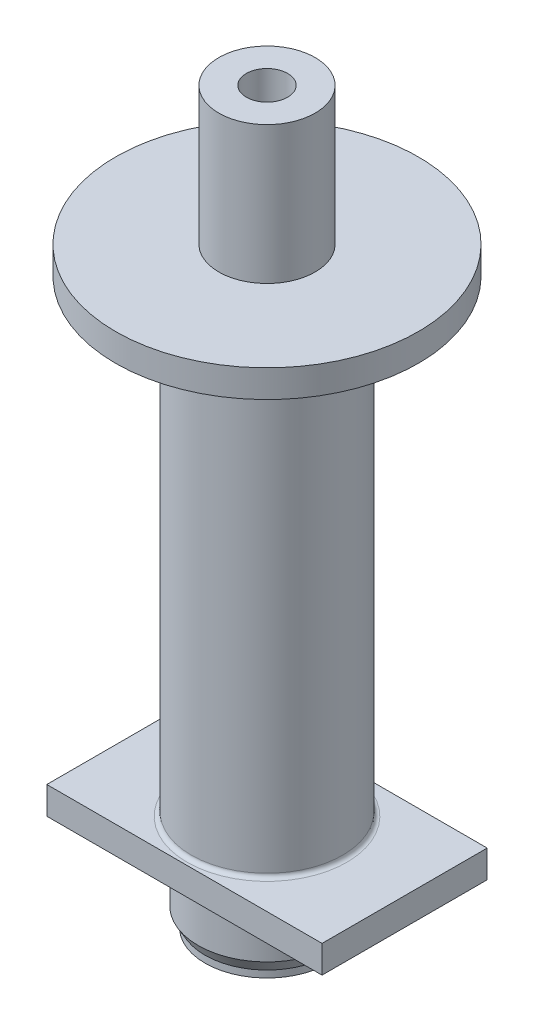
SolidWorks part; units mm, degrees
ref_plane "Front Plane" through (0, 0, 0) normal (0, 0, 1) x (1, 0, 0)
ref_plane "Top Plane" through (0, 0, 0) normal (0, 1, 0) x (1, 0, 0)
ref_plane "Right Plane" through (0, 0, 0) normal (1, 0, 0) x (0, 0, -1)
sketch "Sketch1" plane through (0, 0, 0) normal (0, 0, 1) x (1, 0, 0)
  line L10 (0, 0) -> (-45, 0)
  line L11 (-45, 0) -> (-45, 5)
  line L12 (-45, 5) -> (-50, 13.6603)
  line L13 (-50, 13.6603) -> (-50, 45)
  line L14 (-55, 50) -> (-60, 50)
  line L15 (-60, 50) -> (-60, 70)
  line L16 (-60, 70) -> (-55, 70)
  line L17 (-55, 70) -> (-55, 410)
  line L19 (0, 530) -> (0, 0)
  line L20 (-55, 410) -> (-110, 410)
  line L21 (-110, 410) -> (-110, 430)
  line L22 (-110, 430) -> (-35, 430)
  line L23 (-35, 430) -> (-35, 530)
  line L24 (-35, 530) -> (0, 530)
  arc A1 (-50, 45) -> (-55, 50) centre (-55, 45) ccw
  dimension "D7" = 340
  dimension "D5" = 5
  dimension "D1" = 150
  dimension "D2" = 5
  dimension "D3" = 45
  dimension "D4" = 55
  dimension "D6" = 20
  dimension "D8" = 530
  dimension "D9" = 5
  dimension "D10" = 20
  dimension "D11" = 55
  dimension "D12" = 100
  dimension "D13" = 75
revolve "Revolve1" add sketch "Sketch1" angle 360 about L19
fillet "Fillet1" radius 3 1 edges at (0, 70, 55)
sketch "Sketch3" plane through (0, 0, 0) normal (0, -1, 0) x (1, 0, 0)
  circle A0 centre (0, 0) radius 25
  dimension "D1" = 50
extrude "Cut-Extrude2" cut sketch "Sketch3" against normal blind 410
sketch "Sketch4" plane through (0, 530, 0) normal (0, 1, 0) x (1, 0, 0)
  circle A0 centre (0, 0) radius 15
  dimension "D1" = 30
extrude "Cut-Extrude3" cut sketch "Sketch4" against normal blind 150
ref_plane "Plane1" through (0, 50, 0) normal (0, 1, 0) x (1, 0, 0)
sketch "Sketch6" plane through (0, 50, 0) normal (0, 1, 0) x (1, 0, 0)
  line L0 (0, -60) -> (100, -60)
  line L1 (100, -60) -> (100, 60)
  line L2 (100, 60) -> (-100, 60)
  line L3 (-100, 60) -> (-100, -60)
  line L4 (-100, -60) -> (0, -60)
  circle A0 centre (0, 0) radius 60 construction
  dimension "D1" = 120
  dimension "D2" = 200
  dimension "D3" = 100
  dimension "D4" = 60
extrude "Boss-Extrude1" add sketch "Sketch6" along normal blind 20
